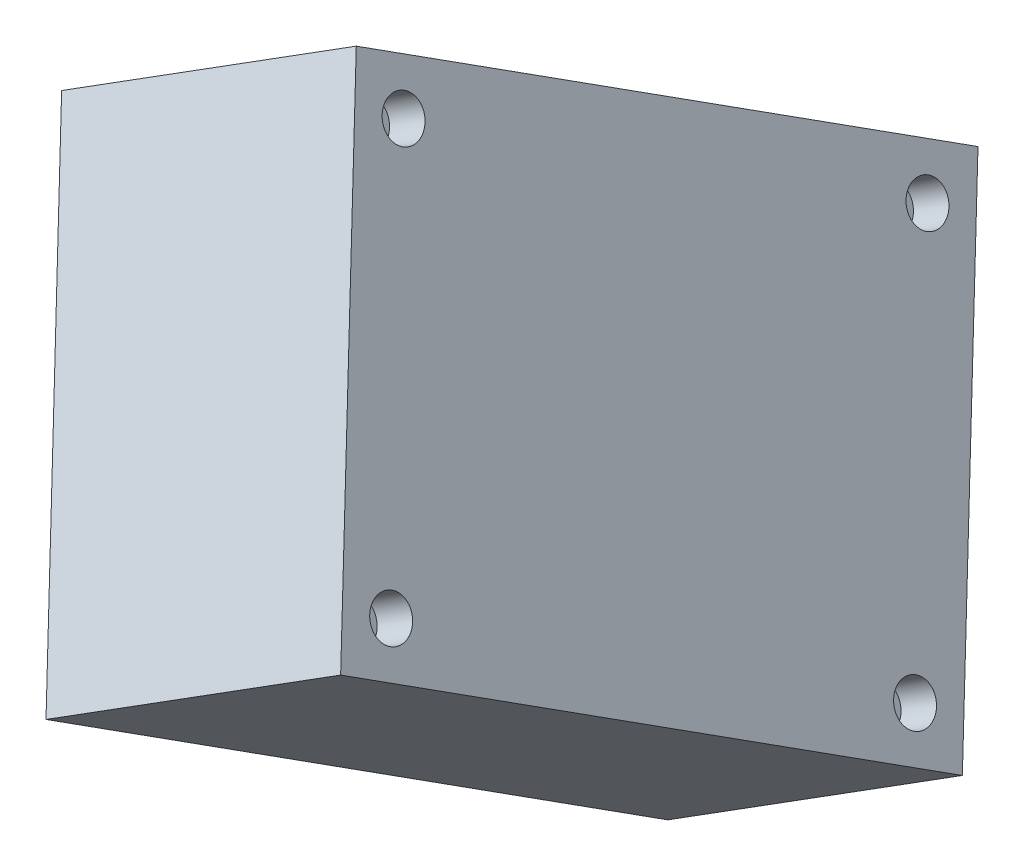
SolidWorks part; units mm, degrees
ref_plane "Front Plane" through (0, 0, 0) normal (0, 0, 1) x (1, 0, 0)
ref_plane "Top Plane" through (0, 0, 0) normal (0, 1, 0) x (1, 0, 0)
ref_plane "Right Plane" through (0, 0, 0) normal (1, 0, 0) x (0, 0, -1)
sketch "Sketch2" plane through (-280.6079, -167.0995, 26.5605) normal (0.8564, 0.51, -0.0811) x (0.2019, -0.4752, -0.8564)
  line L1 (-415.6707, 39.0235) -> (-317.1707, 39.0235)
  line L2 (-415.6707, 39.0235) -> (-415.6707, -36.4765)
  line L3 (-415.6707, -36.4765) -> (-317.1707, -36.4765)
  line L4 (-317.1707, 39.0235) -> (-317.1707, -36.4765)
  line L5 (-415.6707, 39.0235) -> (-317.1707, -36.4765) construction
  line L6 (-415.6707, -36.4765) -> (-317.1707, 39.0235) construction
  point P0 (-366.4207, 1.2735)
  dimension "D1" = 98.5
  dimension "75.5mm" = 75.5
extrude "Boss-Extrude1" add sketch "Sketch2" along normal blind 52.7
sketch "Sketch3" plane through (-235.4772, -140.2246, 22.2887) normal (0.8564, 0.51, -0.0811) x (0.2019, -0.4752, -0.8564)
  line L0 (-415.6707, 39.0235) -> (-415.6707, -36.4765) construction
  line L1 (-317.1707, 39.0235) -> (-415.6707, 39.0235) construction
  line L2 (-407.9207, 31.2735) -> (-324.9207, 31.2735) construction
  line L3 (-407.9207, 31.2735) -> (-407.9207, -28.7265) construction
  line L4 (-407.9207, -28.7265) -> (-324.9207, -28.7265) construction
  line L5 (-324.9207, 31.2735) -> (-324.9207, -28.7265) construction
  line L6 (-407.9207, 31.2735) -> (-324.9207, -28.7265) construction
  line L7 (-407.9207, -28.7265) -> (-324.9207, 31.2735) construction
  circle A0 centre (-407.9207, 31.2735) radius 3.4
  circle A1 centre (-407.9207, -28.7265) radius 3.4
  circle A2 centre (-324.9207, 31.2735) radius 3.4
  circle A3 centre (-324.9207, -28.7265) radius 3.4
  point P1 (-366.4207, 1.2735)
  point P8 (-415.6707, 1.2735)
  point P11 (-366.4207, 39.0235)
  dimension "D1" = 6.8
  dimension "D2" = 6.8
  dimension "D3" = 83
  dimension "D4" = 60
extrude "Cut-Extrude1" cut sketch "Sketch3" against normal blind 6.35
